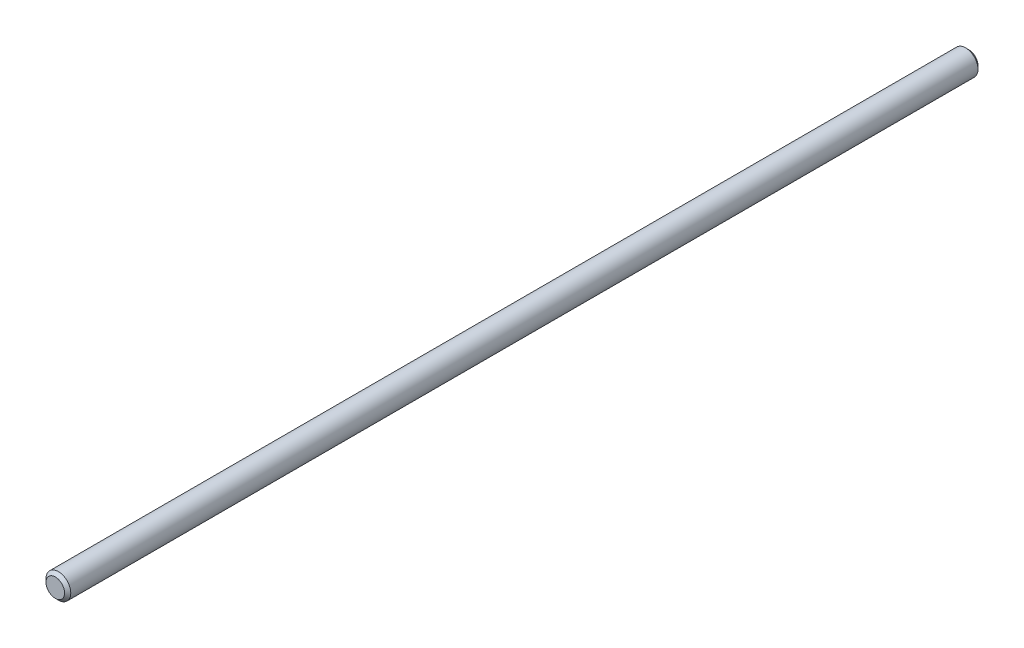
SolidWorks part; units mm, degrees
ref_plane "Front" through (0, 0, 0) normal (0, 0, 1) x (1, 0, 0)
ref_plane "Top" through (0, 0, 0) normal (0, 1, 0) x (1, 0, 0)
ref_plane "Right" through (0, 0, 0) normal (1, 0, 0) x (0, 0, -1)
sketch "Sketch1" plane through (0, 0, 0) normal (0, 0, 1) x (1, 0, 0)
  circle A0 centre (0, 0) radius 4
  dimension "D1" = 8
extrude "Boss-Extrude1" add sketch "Sketch1" along normal blind 295
chamfer "Chamfer1" distance 1 angle 45 2 edges at (4, 0, 295) (4, 0, 0)
